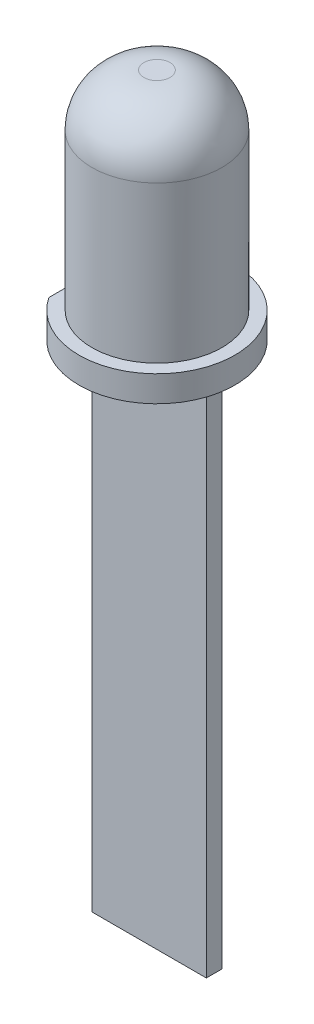
SolidWorks part; units mm, degrees
ref_plane "Front Plane" through (0, 0, 0) normal (0, 0, 1) x (1, 0, 0)
ref_plane "Top Plane" through (0, 0, 0) normal (0, 1, 0) x (1, 0, 0)
ref_plane "Right Plane" through (0, 0, 0) normal (1, 0, 0) x (0, 0, -1)
sketch "Sketch1" plane through (0, 0, 0) normal (0, 1, 0) x (1, 0, 0)
  circle A0 centre (0, 0) radius 3
  dimension "D1" = 6
extrude "Boss-Extrude1" add sketch "Sketch1" along normal blind 1
sketch "Sketch2" plane through (0, 1, 0) normal (0, 1, 0) x (1, 0, 0)
  circle A0 centre (0, 0) radius 2.5
  dimension "D1" = 5
extrude "Boss-Extrude2" add sketch "Sketch2" along normal blind 8
fillet "Fillet1" radius 2 1 edges at (0, 9, 2.5)
sketch "Sketch3" plane through (0, 0, 0) normal (0, -1, 0) x (1, 0, 0)
  line L1 (-2.2, 0.3) -> (2.2, 0.3)
  line L2 (-2.2, 0.3) -> (-2.2, -0.3)
  line L3 (-2.2, -0.3) -> (2.2, -0.3)
  line L4 (2.2, 0.3) -> (2.2, -0.3)
  line L5 (-2.2, 0.3) -> (2.2, -0.3) construction
  line L6 (-2.2, -0.3) -> (2.2, 0.3) construction
  point P0 (0, 0)
  dimension "D1" = 4.4
  dimension "D2" = 0.6
extrude "Boss-Extrude3" add sketch "Sketch3" along normal blind 20
sketch "Sketch4" plane through (0, 0, 0) normal (1, 0, 0) x (0, 0, -1)
  line L1 (7.4499, 2.5121) -> (-7.4499, 2.5121)
  line L2 (7.4499, 2.5121) -> (7.4499, -2.5121)
  line L3 (7.4499, -2.5121) -> (-7.4499, -2.5121)
  line L4 (-7.4499, 2.5121) -> (-7.4499, -2.5121)
  line L5 (7.4499, 2.5121) -> (-7.4499, -2.5121) construction
  line L6 (7.4499, -2.5121) -> (-7.4499, 2.5121) construction
  point P0 (0, 0)
extrude "Cut-Extrude1" cut sketch "Sketch4" against normal blind 20 from offset 2.5
